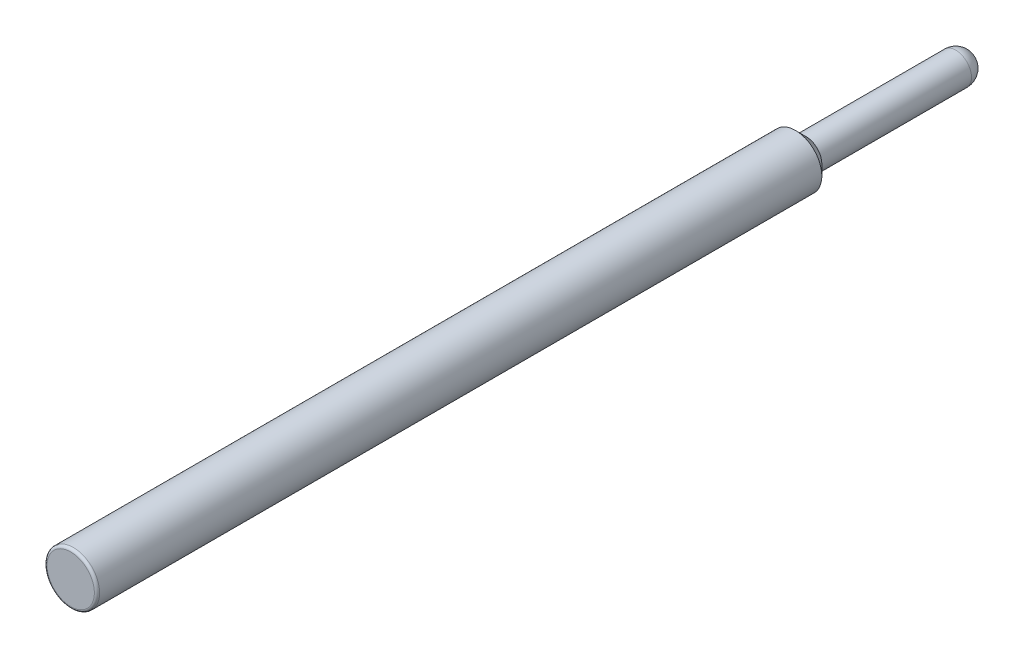
SolidWorks part; units mm, degrees
ref_plane "Front Plane" through (0, 0, 0) normal (0, 0, 1) x (1, 0, 0)
ref_plane "Top Plane" through (0, 0, 0) normal (0, 1, 0) x (1, 0, 0)
ref_plane "Right Plane" through (0, 0, 0) normal (1, 0, 0) x (0, 0, -1)
sketch "Sketch1" plane through (0, 0, 0) normal (0, 1, 0) x (1, 0, 0)
  line L0 (0, 347.3781) -> (0, -272.7425) construction
  line L1 (0, 0) -> (9, 0)
  line L2 (10, 1) -> (10, 276)
  line L3 (0, 0) -> (0, 343)
  line L5 (10, 276) -> (6, 280)
  line L6 (6, 280) -> (6, 337)
  arc A0 (6, 337) -> (0, 343) centre (0, 337) ccw
  arc A1 (9, 0) -> (10, 1) centre (9, 1) ccw
  dimension "D5" = 6
  dimension "D7" = 1
  dimension "D1" = 280
  dimension "D2" = 20
  dimension "D3" = 12
  dimension "D4" = 4
  dimension "D6" = 63
  dimension "D8" = 45
revolve "Revolve1" add sketch "Sketch1" angle 360 about L0
